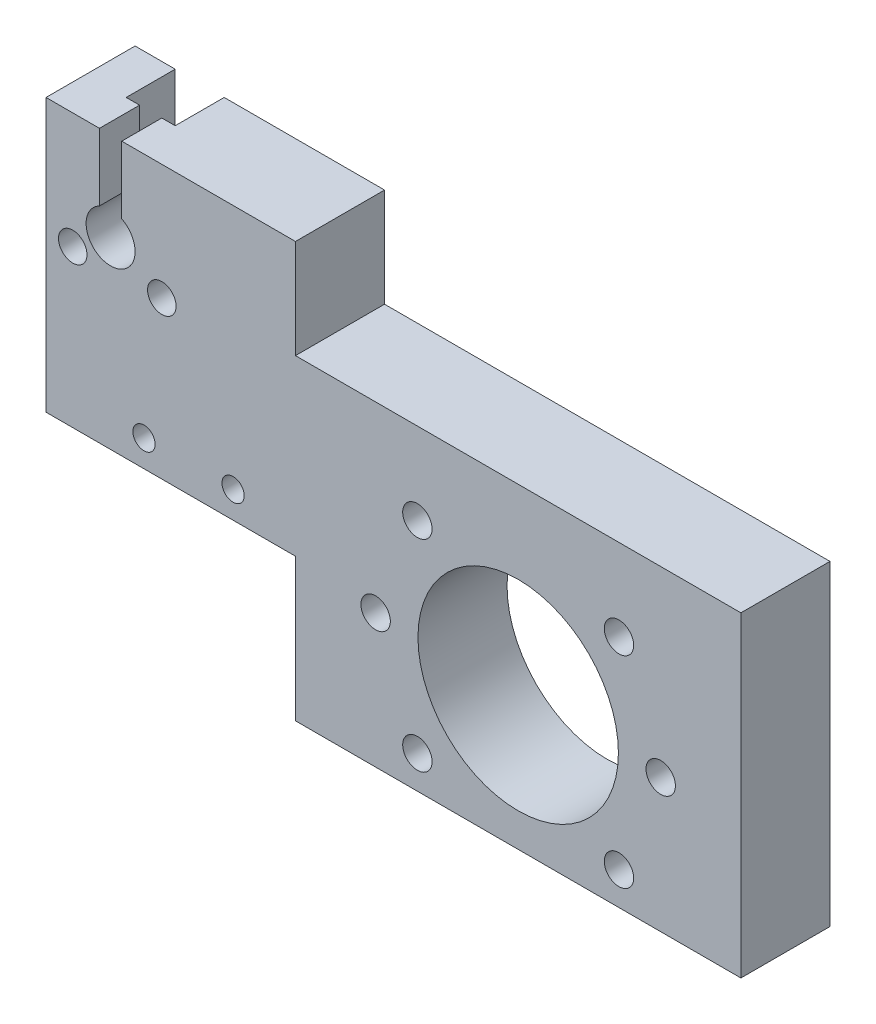
SolidWorks part; units mm, degrees
ref_plane "前视基准面" through (0, 0, 0) normal (0, 0, 1) x (1, 0, 0)
ref_plane "上视基准面" through (0, 0, 0) normal (0, 1, 0) x (1, 0, 0)
ref_plane "右视基准面" through (0, 0, 0) normal (1, 0, 0) x (0, 0, -1)
other "Configuration Table"
sketch "草图1" plane through (0, 0, 0) normal (0, 0, 1) x (1, 0, 0)
  line L1 (-25, 17.75) -> (25, 17.75)
  line L2 (-25, 17.75) -> (-25, -17.75)
  line L3 (-25, -17.75) -> (25, -17.75)
  line L4 (25, 17.75) -> (25, -17.75)
  line L5 (0, -17.75) -> (0, 17.75) construction
  line L6 (-25, 0) -> (25, 0) construction
  point P0 (0, 0)
  dimension "D1" = 35.5
  dimension "D2" = 50
extrude "凸台-拉伸1" add sketch "草图1" along normal blind 10
sketch "草图2" plane through (0, 0, 10) normal (0, 0, 1) x (1, 0, 0)
  line L0 (-25, -17.75) -> (25, -17.75) construction
  circle A0 centre (0, -2.75) radius 11.25
  dimension "D1" = 22.5
  dimension "D2" = 15
extrude "切除-拉伸1" cut sketch "草图2" against normal through all
sketch "草图3" plane through (0, 0, 10) normal (0, 0, 1) x (1, 0, 0)
  circle A1 centre (0, -2.75) radius 16 construction
  circle A2 centre (-16, -2.75) radius 1.65
  circle A3 centre (-11.3137, 8.5637) radius 1.65
  circle A4 centre (0, 13.25) radius 1.65 construction
  circle A5 centre (11.3137, 8.5637) radius 1.65
  circle A6 centre (16, -2.75) radius 1.65
  circle A7 centre (11.3137, -14.0637) radius 1.65
  circle A8 centre (0, -18.75) radius 1.65 construction
  circle A9 centre (-11.3137, -14.0637) radius 1.65
  point P22 (0, -2.75)
  dimension "D1" = 32
  dimension "D2" = 3.3
  dimension "D3" = 8
extrude "切除-拉伸2" cut sketch "草图3" against normal through all
sketch "草图4" plane through (0, 0, 10) normal (0, 0, 1) x (1, 0, 0)
  line L9 (-25, -17.75) -> (25, -17.75) construction
  line L10 (-25, 17.75) -> (-50, 17.75)
  line L11 (-25, 17.75) -> (-25, -1.75)
  line L12 (-25, -1.75) -> (-50, -1.75)
  line L13 (-50, 17.75) -> (-50, -1.75)
  dimension "D1" = 25
  dimension "D2" = 16
extrude "凸台-拉伸2" add sketch "草图4" against normal blind 10
sketch "草图5" plane through (0, 0, 0) normal (0, 0, -1) x (-1, 0, 0)
  line L0 (50, 1.25) -> (25, 1.25) construction
  line L1 (50, 17.75) -> (50, -1.75) construction
  line L2 (50, -1.75) -> (25, -1.75) construction
  circle A0 centre (42, 1.25) radius 1.25
  circle A1 centre (32, 1.25) radius 1.25
  dimension "D3" = 2.5
  dimension "D1" = 25
  dimension "D2" = 3
  dimension "D4" = 8
  dimension "D5" = 10
extrude "切除-拉伸3" cut sketch "草图5" against normal blind 10
sketch "草图7" plane through (0, 17.75, 0) normal (0, 1, 0) x (1, 0, 0)
  line L0 (25, -10) -> (-50, -10) construction
  line L1 (-50, 0) -> (-25, 0)
  line L2 (-50, 0) -> (-50, -10)
  line L3 (-50, -10) -> (-25, -10)
  line L4 (-25, 0) -> (-25, -10)
  dimension "D1" = 25
extrude "凸台-拉伸4" add sketch "草图7" along normal blind 11.1
sketch "草图8" plane through (0, 0, 0) normal (0, 0, -1) x (-1, 0, 0)
  line L0 (25, 28.85) -> (50, 28.85) construction
  line L1 (44.5, 28.85) -> (47, 28.85)
  line L2 (44.5, 28.85) -> (44.5, 18.85)
  line L3 (44.5, 18.85) -> (47, 18.85)
  line L4 (47, 28.85) -> (47, 18.85)
  line L5 (50, 28.85) -> (50, -1.75) construction
  dimension "D1" = 2.5
  dimension "D2" = 10
  dimension "D3" = 3
extrude "切除-拉伸4" cut sketch "草图8" against normal through all
sketch "草图9" plane through (0, 0, 0) normal (0, 0, -1) x (-1, 0, 0)
  line L0 (25, 28.85) -> (44.5, 28.85) construction
  line L1 (43, 28.85) -> (48.5, 28.85)
  line L2 (43, 28.85) -> (43, 18.85)
  line L3 (43, 18.85) -> (48.5, 18.85)
  line L4 (48.5, 28.85) -> (48.5, 18.85)
  line L5 (50, 28.85) -> (50, -1.75) construction
  dimension "D1" = 5.5
  dimension "D2" = 1.5
  dimension "D3" = 10
extrude "切除-拉伸5" cut sketch "草图9" against normal blind 5.5
sketch "草图10" plane through (-50, 0, 0) normal (-1, 0, 0) x (0, 0, 1)
  line L4 (10, -1.75) -> (10, 28.85)
  line L5 (10, 28.85) -> (0, 28.85)
  line L6 (0, 28.85) -> (0, -1.75)
  line L7 (0, -1.75) -> (10, -1.75)
  line L8 (10, -1.75) -> (10, 28.85)
  line L9 (10, 28.85) -> (0, 28.85)
  line L10 (0, 28.85) -> (0, -1.75)
  line L11 (0, -1.75) -> (10, -1.75)
  dimension "D1" = 0
extrude "凸台-拉伸5" add sketch "草图10" along normal blind 3
sketch "草图11" plane through (0, 0, 0) normal (0, 0, -1) x (-1, 0, 0)
  line L1 (43, 18.85) -> (48.5, 18.85) construction
  line L2 (48.5, 18.85) -> (48.5, 28.85) construction
  line L3 (48.5, 28.85) -> (53, 28.85) construction
  circle A1 centre (45.75, 18.85) radius 2.75
  point P2 (0, 0)
  point P6 (45.75, 18.85)
  dimension "D1" = 10
extrude "切除-拉伸6" cut sketch "草图11" against normal through all
sketch "草图13" plane through (0, 0, 10) normal (0, 0, 1) x (1, 0, 0)
  line L0 (-53, 15.85) -> (25, 15.85) construction
  line L1 (-53, -1.75) -> (-53, 28.85) construction
  line L2 (25, -17.75) -> (25, 17.75) construction
  line L3 (-44.5, 28.85) -> (-25, 28.85) construction
  circle A0 centre (-50, 15.85) radius 1.6
  circle A1 centre (-40, 15.85) radius 1.6
  point P14 (-41.5, 15.85)
  dimension "D2" = 3.2
  dimension "D3" = 3.2
  dimension "D1" = 13
  dimension "D4" = 3
  dimension "D5" = 10
extrude "切除-拉伸8" cut sketch "草图13" against normal through all contours A1 | A0
